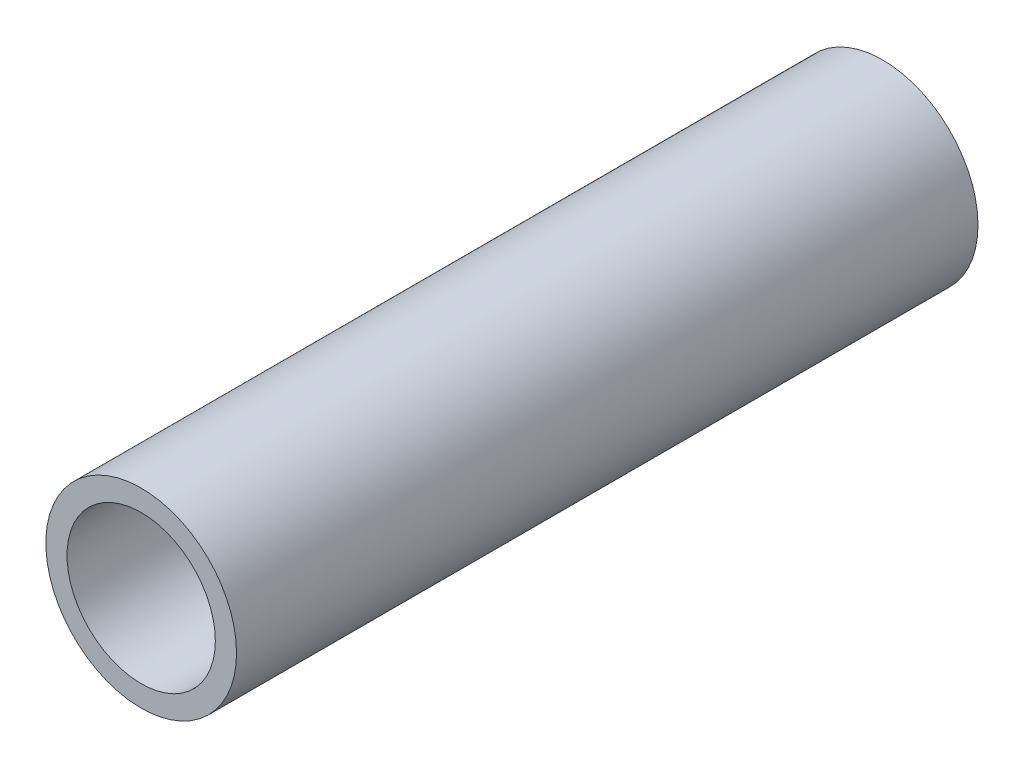
SolidWorks part; units mm, degrees
ref_plane "前视基准面" through (0, 0, 0) normal (0, 0, 1) x (1, 0, 0)
ref_plane "上视基准面" through (0, 0, 0) normal (0, 1, 0) x (1, 0, 0)
ref_plane "右视基准面" through (0, 0, 0) normal (1, 0, 0) x (0, 0, -1)
sketch "草图1" plane through (0, 0, 0) normal (0, 1, 0) x (1, 0, 0)
  line L0 (9, 0) -> (7, 0)
  line L1 (7, 0) -> (7, -70)
  line L2 (7, -70) -> (9, -70)
  line L3 (9, -70) -> (9, 0)
  line L4 (0, 0) -> (0, -70) construction
revolve "旋转1" add sketch "草图1" angle 360 about L4
